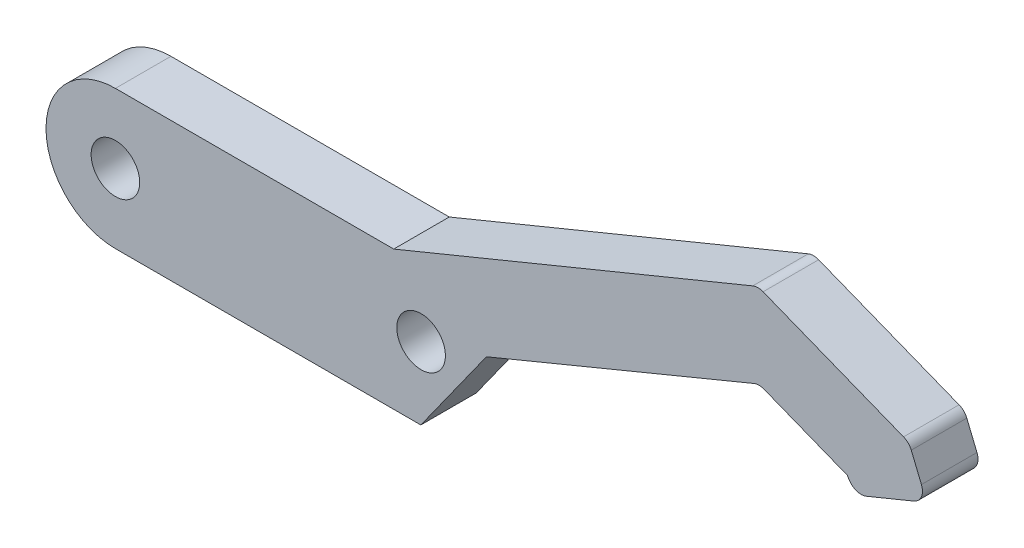
SolidWorks part; units mm, degrees
ref_plane "Front Plane" through (0, 0, 0) normal (0, 0, 1) x (1, 0, 0)
ref_plane "Top Plane" through (0, 0, 0) normal (0, 1, 0) x (1, 0, 0)
ref_plane "Right Plane" through (0, 0, 0) normal (1, 0, 0) x (0, 0, -1)
sketch "Sketch1" plane through (0, 0, 0) normal (0, 0, 1) x (1, 0, 0)
  line L0 (0, 0) -> (22, 0) construction
  line L1 (0, 5) -> (22, 5)
  line L2 (0, -5) -> (22, -5)
  line L3 (20.05, 5) -> (23.9914, -4.5863) construction
  line L4 (20.05, 5) -> (46.2838, 15.786) construction
  line L5 (23.9914, -4.5863) -> (52.7188, 7.2249) construction
  line L7 (20.05, 5) -> (46.2838, 15.786)
  line L10 (52.7188, 7.2249) -> (46.3588, 9.7358)
  line L11 (46.3588, 9.7358) -> (26.7294, 1.6226)
  line L12 (58.4433, 8.3892) -> (53.3297, 6.2868)
  line L13 (52.7188, 7.2249) -> (53.3297, 6.2868)
  line L14 (46.2838, 15.786) -> (57.169, 11.4886)
  line L15 (57.169, 11.4886) -> (58.4433, 8.3892)
  line L24 (26.7294, 1.6226) -> (22, -5)
  line L25 (36.5441, 5.6792) -> (55.643, -40.5294) construction
  arc A0 (0, 5) -> (0, -5) centre (0, 0) ccw
  arc A1 (22, -5) -> (22, 5) centre (22, 0) ccw
  circle A2 centre (0, 0) radius 1.5
  circle A3 centre (22.0207, 0.2068) radius 1.5
  point P3 (11, 0)
  dimension "D11" = 3
  dimension "D1" = 10
  dimension "D2" = 22
  dimension "D3" = 157.65
  dimension "D4" = 1.95
  dimension "D9" = 136
  dimension "D10" = 21.24
  dimension "D13" = 5.6
extrude "Boss-Extrude3" add sketch "Sketch1" along normal blind 4
fillet "Congé3" radius 1 3 edges at (46.3588, 9.7358, 2) (53.3297, 6.2868, 2) (58.4433, 8.3892, 2)
fillet "Congé4" radius 1 2 edges at (57.169, 11.4886, 2) (46.2838, 15.786, 2)
sketch "Esquisse1" plane through (0, 0, 4) normal (0, 0, 1) x (1, 0, 0)
  circle A0 centre (22.0207, 0.2068) radius 1.75
  circle A1 centre (0, 0) radius 1.75
extrude "Enlèv. mat.-Extru.1" cut sketch "Esquisse1" against normal blind 10
